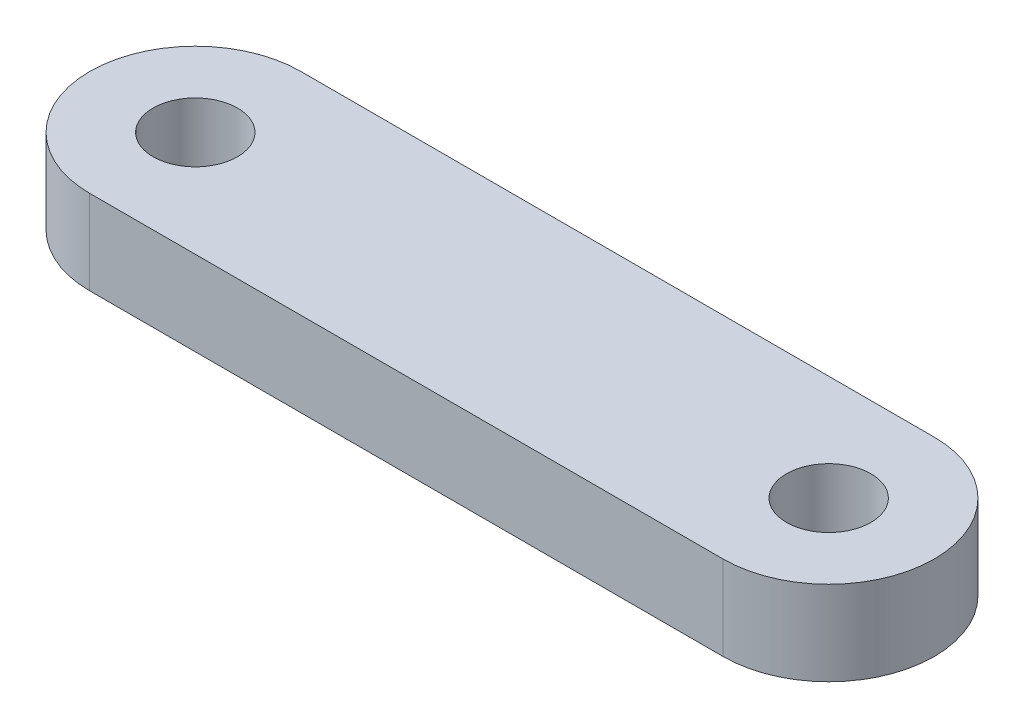
SolidWorks part; units mm, degrees
ref_plane "Front Plane" through (0, 0, 0) normal (0, 0, 1) x (1, 0, 0)
ref_plane "Top Plane" through (0, 0, 0) normal (0, 1, 0) x (1, 0, 0)
ref_plane "Right Plane" through (0, 0, 0) normal (1, 0, 0) x (0, 0, -1)
sketch "Sketch1" plane through (0, 0, 0) normal (0, 1, 0) x (1, 0, 0)
  line L0 (-10, 0) -> (5, 0) construction
  line L1 (-10, 2.5) -> (5, 2.5)
  line L2 (-10, -2.5) -> (5, -2.5)
  arc A0 (-10, 2.5) -> (-10, -2.5) centre (-10, 0) ccw
  arc A1 (5, -2.5) -> (5, 2.5) centre (5, 0) ccw
  circle A2 centre (5, 0) radius 1
  circle A3 centre (-10, 0) radius 1
  point P3 (-2.5, 0)
  dimension "D3" = 2
  dimension "D4" = 2.5
  dimension "D5" = 2
  dimension "D1" = 15
  dimension "D12" = 10
extrude "Boss-Extrude1" add sketch "Sketch1" along normal blind 2
